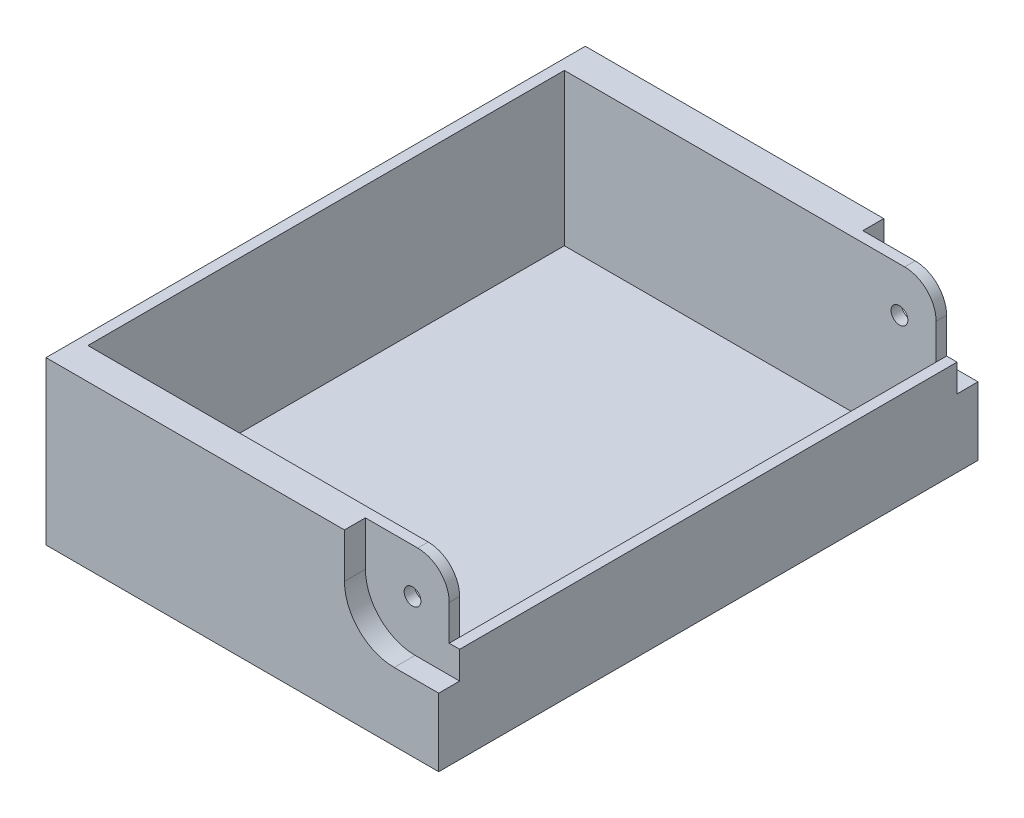
SolidWorks part; units mm, degrees
ref_plane "前视基准面" through (0, 0, 0) normal (0, 0, 1) x (1, 0, 0)
ref_plane "上视基准面" through (0, 0, 0) normal (0, 1, 0) x (1, 0, 0)
ref_plane "右视基准面" through (0, 0, 0) normal (1, 0, 0) x (0, 0, -1)
sketch "草图1" plane through (0, 0, 0) normal (0, 1, 0) x (1, 0, 0)
  line L1 (-59.1667, 41.7998) -> (15.8333, 41.7998)
  line L2 (-59.1667, 41.7998) -> (-59.1667, -53.2002)
  line L3 (-59.1667, -53.2002) -> (15.8333, -53.2002)
  line L4 (15.8333, 41.7998) -> (15.8333, -53.2002)
  line L5 (-59.1667, 41.7998) -> (15.8333, -53.2002) construction
  line L6 (-59.1667, -53.2002) -> (15.8333, 41.7998) construction
  point P4 (-21.6667, -5.7002)
  dimension "D1" = 95
  dimension "D2" = 75
extrude "凸台-拉伸1" add sketch "草图1" along normal blind 25
shell "抽壳1" thickness 2
sketch "草图2" plane through (0, 0, 53.2002) normal (0, 0, 1) x (1, 0, 0)
  line L1 (-59.1667, 0) -> (15.8333, 0)
  line L2 (-59.1667, 0) -> (-59.1667, 25)
  line L3 (-59.1667, 25) -> (15.8333, 25)
  line L4 (15.8333, 0) -> (15.8333, 25)
  line L5 (-59.1667, 0) -> (15.8333, 25) construction
  line L6 (-59.1667, 25) -> (15.8333, 0) construction
  point P4 (-21.6667, 12.5)
extrude "凸台-拉伸2" add sketch "草图2" along normal blind 4
sketch "草图3" plane through (0, 0, -41.7998) normal (0, 0, -1) x (-1, 0, 0)
  line L1 (-15.8333, 25) -> (59.1667, 25)
  line L2 (-15.8333, 25) -> (-15.8333, 0)
  line L3 (-15.8333, 0) -> (59.1667, 0)
  line L4 (59.1667, 25) -> (59.1667, 0)
  line L5 (-15.8333, 25) -> (59.1667, 0) construction
  line L6 (-15.8333, 0) -> (59.1667, 25) construction
  point P4 (21.6667, 12.5)
extrude "凸台-拉伸3" add sketch "草图3" along normal blind 4
sketch "草图4" plane through (0, 0, -45.7998) normal (0, 0, -1) x (-1, 0, 0)
  line L1 (-15.8333, 25) -> (1.1667, 25) construction
  line L2 (-15.8333, 25) -> (-15.8333, 8) construction
  line L3 (-15.8333, 8) -> (1.1667, 8) construction
  line L4 (1.1667, 25) -> (1.1667, 8) construction
  line L5 (-15.8333, 25) -> (1.1667, 8) construction
  line L6 (-15.8333, 8) -> (1.1667, 25) construction
  line L9 (-16.8333, 26) -> (-16.8333, 16.5)
  line L10 (2.1667, 7) -> (-16.8333, 7) construction
  line L11 (2.1667, 7) -> (2.1667, 26) construction
  line L12 (2.1667, 26) -> (-16.8333, 26)
  line L13 (-16.8333, 7) -> (-16.8333, 26) construction
  line L14 (2.1667, 7) -> (-16.8333, 26) construction
  line L15 (2.1667, 26) -> (-16.8333, 7) construction
  line L16 (2.1667, 26) -> (2.1667, 16.5)
  arc A0 (1.1667, 16.5) -> (-15.8333, 16.5) centre (-7.3333, 16.5) cw construction
  arc A1 (-16.8333, 16.5) -> (2.1667, 16.5) centre (-7.3333, 16.5) ccw
  point P4 (-7.3333, 16.5)
  point P6 (1.1667, 16.5)
  point P7 (-15.8333, 16.5)
  point P8 (-7.3333, 8)
  point P17 (2.1667, 16.5)
  point P18 (-16.8333, 16.5)
  point P19 (-7.3333, 7)
  dimension "D1" = 17
  dimension "D2" = 17
  dimension "D3" = 19
  dimension "D4" = 19
extrude "切除-拉伸2" cut sketch "草图4" against normal blind 4
sketch "草图5" plane through (0, 0, 57.2002) normal (0, 0, 1) x (1, 0, 0)
  line L0 (16.8333, 26) -> (-2.1667, 26) construction
  line L1 (15.8333, 25) -> (-1.1667, 25) construction
  line L2 (15.8333, 25) -> (15.8333, 8) construction
  line L3 (15.8333, 8) -> (-1.1667, 8) construction
  line L4 (-1.1667, 25) -> (-1.1667, 8) construction
  line L5 (15.8333, 25) -> (-1.1667, 8) construction
  line L6 (15.8333, 8) -> (-1.1667, 25) construction
  line L7 (16.8333, 26) -> (16.8333, 7) construction
  line L8 (16.8333, 7) -> (-2.1667, 7) construction
  line L9 (-2.1667, 26) -> (-2.1667, 7) construction
  line L10 (16.8333, 26) -> (-2.1667, 7) construction
  line L11 (16.8333, 7) -> (-2.1667, 26) construction
  line L12 (-2.1667, 26) -> (-2.1667, 16.5)
  line L13 (-2.1667, 26) -> (16.8333, 26)
  line L14 (16.8333, 26) -> (16.8333, 16.5)
  arc A0 (-1.1667, 16.5) -> (15.8333, 16.5) centre (7.3333, 16.5) ccw construction
  arc A1 (-2.1667, 16.5) -> (16.8333, 16.5) centre (7.3333, 16.5) ccw
  point P4 (7.3333, 16.5)
  point P6 (-1.1667, 16.5)
  point P7 (15.8333, 16.5)
  point P8 (7.3333, 8)
  point P17 (-2.1667, 16.5)
  point P18 (16.8333, 16.5)
  point P19 (7.3333, 7)
  dimension "D1" = 17
  dimension "D2" = 17
  dimension "D3" = 19
  dimension "D4" = 19
extrude "切除-拉伸3" cut sketch "草图5" against normal blind 4
sketch "草图6" plane through (0, 0, 53.2002) normal (0, 0, 1) x (1, 0, 0)
  line L0 (-2.1667, 16.5) -> (15.8333, 16.5) construction
  line L2 (-2.1667, 25) -> (15.8333, 25) construction
  line L3 (15.8333, 25) -> (-2.1667, 16.5) construction
  line L4 (-2.1667, 16.5) -> (-2.1667, 25) construction
  line L5 (6.8333, 25) -> (6.8333, 16.5) construction
  line L6 (15.8333, 12.2574) -> (15.8333, 25) construction
  line L7 (15.8333, 16.5) -> (-2.1667, 25) construction
  circle A0 centre (6.8333, 16.5) radius 1.6
  point P5 (6.8333, 25)
extrude "切除-拉伸4" cut sketch "草图6" against normal blind 150
sketch "草图7" plane through (15.8333, 0, 0) normal (1, 0, 0) x (0, 0, -1)
  line L1 (-53.2002, 25) -> (41.7998, 25)
  line L2 (-53.2002, 25) -> (-53.2002, 12.2574)
  line L3 (-53.2002, 12.2574) -> (41.7998, 12.2574)
  line L4 (41.7998, 25) -> (41.7998, 12.2574)
  line L5 (-53.2002, 25) -> (41.7998, 12.2574) construction
  line L6 (-53.2002, 12.2574) -> (41.7998, 25) construction
  point P4 (-5.7002, 18.6287)
extrude "切除-拉伸5" cut sketch "草图7" against normal blind 2
sketch "草图8" plane through (0, 0, -45.7998) normal (0, 0, -1) x (-1, 0, 0)
  line L0 (-7.3333, 7) -> (-15.8333, 7)
  line L1 (-15.8333, 12.2574) -> (-15.8333, 0) construction
  line L2 (-15.8333, 7) -> (-15.8333, 12.2574)
  line L3 (-15.8333, 12.2574) -> (-7.3333, 7)
  arc A0 (-15.8333, 12.2574) -> (2.1667, 16.5) centre (-7.3333, 16.5) ccw construction
  arc A1 (-15.8333, 12.2574) -> (2.1667, 16.5) centre (-7.3333, 16.5) ccw construction
extrude "切除-拉伸6" cut sketch "草图8" against normal blind 4
sketch "草图9" plane through (0, 0, 57.2002) normal (0, 0, 1) x (1, 0, 0)
  line L0 (7.3333, 7) -> (15.8333, 7)
  line L1 (15.8333, 0) -> (15.8333, 12.2574) construction
  line L2 (15.8333, 7) -> (15.8333, 12.2574)
  line L3 (15.8333, 12.2574) -> (7.3333, 7)
  arc A0 (-2.1667, 16.5) -> (15.8333, 12.2574) centre (7.3333, 16.5) ccw construction
  arc A1 (-2.1667, 16.5) -> (15.8333, 12.2574) centre (7.3333, 16.5) ccw construction
extrude "切除-拉伸7" cut sketch "草图9" against normal blind 4
sketch "草图10" plane through (0, 0, -41.7998) normal (0, 0, -1) x (-1, 0, 0)
  line L0 (-5.8333, 25) -> (-7.8333, 25) construction
  line L2 (-13.8333, 19) -> (-13.8333, 18.6287)
  line L3 (-13.8333, 12.2574) -> (-13.8333, 25) construction
  line L4 (-7.8333, 25) -> (-13.8333, 25)
  line L5 (-13.8333, 25) -> (-7.8333, 25)
  arc A0 (-13.8333, 19) -> (-7.8333, 25) centre (-7.8333, 19) cw
  point P10 (-13.8333, 25)
  line M9 (2.1667, 25) -> (-13.8333, 25)
  line M10 (-13.8333, 25) -> (-13.8333, 12.2574)
  dimension "D1" = 6
extrude "切除-拉伸9" cut sketch "草图10" against normal blind 150 contours A0 M10 M9
sketch "草图11" plane through (0, 0, 0) normal (0, -1, 0) x (1, 0, 0)
  line L1 (-59.1667, 57.2002) -> (15.8333, 57.2002)
  line L2 (-59.1667, 57.2002) -> (-59.1667, -45.7998)
  line L3 (-59.1667, -45.7998) -> (15.8333, -45.7998)
  line L4 (15.8333, 57.2002) -> (15.8333, -45.7998)
  line L5 (-59.1667, 57.2002) -> (15.8333, -45.7998) construction
  line L6 (-59.1667, -45.7998) -> (15.8333, 57.2002) construction
  point P4 (-21.6667, 5.7002)
extrude "凸台-拉伸4" add sketch "草图11" along normal blind 6
sketch "草图12" plane through (0, 2, 0) normal (0, 1, 0) x (1, 0, 0)
  line L1 (-57.1667, 39.7998) -> (13.8333, 39.7998)
  line L2 (-57.1667, 39.7998) -> (-57.1667, -51.2002)
  line L3 (-57.1667, -51.2002) -> (13.8333, -51.2002)
  line L4 (13.8333, 39.7998) -> (13.8333, -51.2002)
  line L5 (-57.1667, 39.7998) -> (13.8333, -51.2002) construction
  line L6 (-57.1667, -51.2002) -> (13.8333, 39.7998) construction
  point P4 (-21.6667, -5.7002)
extrude "切除-拉伸10" cut sketch "草图12" against normal blind 6
